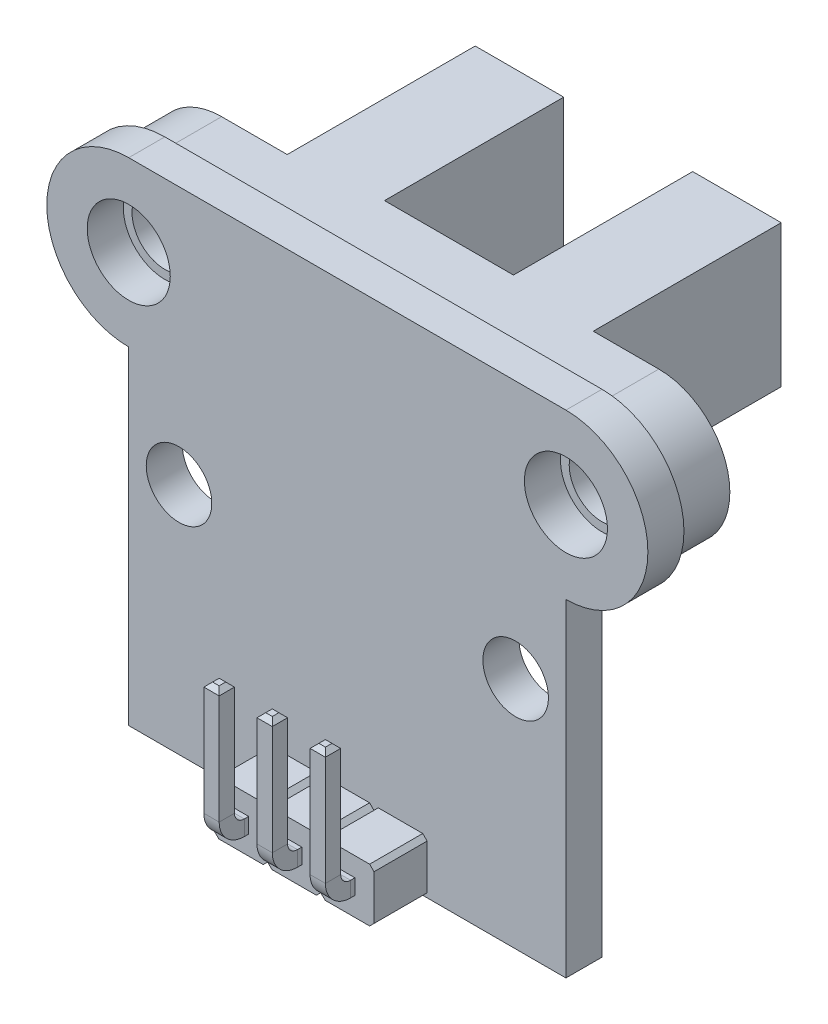
SolidWorks part; units mm, degrees
ref_plane "Ön Düzlem" through (0, 0, 0) normal (0, 0, 1) x (1, 0, 0)
ref_plane "Üst Düzlem" through (0, 0, 0) normal (0, 1, 0) x (1, 0, 0)
ref_plane "Sağ Düzlem" through (0, 0, 0) normal (1, 0, 0) x (0, 0, -1)
sketch "Sketch1" plane through (0, 0, 0) normal (0, 0, 1) x (1, 0, 0)
  line L0 (-10, 0) -> (10, 0) construction
  line L1 (-10, 3.75) -> (10, 3.75)
  line L2 (-10, -3.75) -> (10, -3.75)
  line L3 (10, -3.75) -> (10, -18.75)
  line L4 (10, -18.75) -> (-10, -18.75)
  line L5 (-10, -18.75) -> (-10, -3.75)
  arc A0 (-10, 3.75) -> (-10, -3.75) centre (-10, 0) ccw
  arc A1 (10, -3.75) -> (10, 3.75) centre (10, 0) ccw
  point P2 (0, 0)
  dimension "D1" = 27.5
  dimension "D2" = 7.5
  dimension "D3" = 15
sketch "Sketch2" plane through (0, 0, 0) normal (0, 0, 1) x (1, 0, 0)
  line L0 (-10, -18.75) -> (-10, -3.75) construction
  line L1 (10, -18.75) -> (-10, -18.75) construction
  line L2 (10, -3.75) -> (10, -18.75) construction
  line L3 (-10, 3.75) -> (10, 3.75) construction
  line L4 (-10, -18.75) -> (-10, -3.75)
  line L5 (10, -18.75) -> (-10, -18.75)
  line L6 (10, -3.75) -> (10, -18.75)
  line L7 (-10, 3.75) -> (10, 3.75)
  line L8 (0, 0) -> (0, -18.75) construction
  arc A0 (10, -3.75) -> (10, 3.75) centre (10, 0) ccw construction
  arc A1 (-10, 3.75) -> (-10, -3.75) centre (-10, 0) ccw construction
  arc A2 (10, -3.75) -> (10, 3.75) centre (10, 0) ccw
  arc A3 (-10, 3.75) -> (-10, -3.75) centre (-10, 0) ccw
  circle A4 centre (10, 0) radius 1.9
  circle A5 centre (-10, 0) radius 1.9
  circle A6 centre (7.7, -8.05) radius 1.5
  circle A7 centre (-7.7, -8.05) radius 1.5
  dimension "D1" = 3.8
  dimension "D2" = 0.8
  dimension "D3" = 9.2
  dimension "D4" = 3
extrude "Boss-Extrude1" add sketch "Sketch2" along normal blind 1.65
sketch "Sketch3" plane through (0, 0, 1.65) normal (0, 0, 1) x (1, 0, 0)
  line L0 (-10, -18.75) -> (10, -18.75) construction
  line L1 (3.45, -18.75) -> (1.4167, -18.75)
  line L2 (3.65, -18.55) -> (3.65, -16.5)
  line L3 (3.45, -16.3) -> (1.4167, -16.3)
  line L4 (-3.65, -18.55) -> (-3.65, -16.5)
  line L5 (1.2167, -16.3) -> (1.2167, -18.75) construction
  line L6 (-1.2167, -16.3) -> (-1.2167, -18.75) construction
  line L7 (-1.4167, -16.3) -> (-1.2167, -16.5)
  line L8 (-1.4167, -18.75) -> (-1.2167, -18.55)
  line L9 (-1.2167, -17.525) -> (-0.4992, -17.525) construction
  line L10 (-1.0167, -18.75) -> (-1.2167, -18.55)
  line L11 (-1.0167, -16.3) -> (-1.2167, -16.5)
  line L12 (0, 18.75) -> (0, -18.75) construction
  line L13 (1.0167, -18.75) -> (1.2167, -18.55)
  line L14 (1.4167, -18.75) -> (1.2167, -18.55)
  line L15 (1.0167, -16.3) -> (1.2167, -16.5)
  line L16 (1.4167, -16.3) -> (1.2167, -16.5)
  line L17 (3.65, -16.5) -> (3.45, -16.3)
  line L18 (3.65, -18.55) -> (3.45, -18.75)
  line L19 (-3.45, -18.75) -> (-3.65, -18.55)
  line L20 (-3.45, -16.3) -> (-3.65, -16.5)
  line L21 (-1.4167, -16.3) -> (-3.45, -16.3)
  line L22 (-1.4167, -18.75) -> (-3.45, -18.75)
  line L23 (1.0167, -18.75) -> (-1.0167, -18.75)
  line L24 (1.0167, -16.3) -> (-1.0167, -16.3)
  line L25 (-2.4333, -18.75) -> (-2.4333, -16.3) construction
  line L26 (0.3467, -17.175) -> (0.3467, -17.875)
  line L27 (-2.0833, -17.175) -> (-2.7833, -17.175)
  line L28 (-2.0833, -17.175) -> (-2.0833, -17.875)
  line L29 (-2.0833, -17.875) -> (-2.7833, -17.875)
  line L30 (-2.7833, -17.175) -> (-2.7833, -17.875)
  line L31 (-2.0833, -17.175) -> (-2.7833, -17.875) construction
  line L32 (-2.0833, -17.875) -> (-2.7833, -17.175) construction
  line L33 (0.3467, -17.175) -> (-0.3533, -17.175)
  line L34 (-0.3533, -17.175) -> (-0.3533, -17.875)
  line L35 (0.3467, -17.875) -> (-0.3533, -17.875)
  line L36 (2.7767, -17.175) -> (2.7767, -17.875)
  line L37 (2.7767, -17.175) -> (2.0767, -17.175)
  line L38 (2.0767, -17.175) -> (2.0767, -17.875)
  line L39 (2.7767, -17.875) -> (2.0767, -17.875)
  point P0 (3.65, -18.75)
  point P1 (-3.65, -16.3)
  point P2 (3.65, -16.3)
  point P3 (-3.65, -18.75)
  point P39 (-2.4333, -17.525)
extrude "Boss-Extrude2" add sketch "Sketch3" along normal blind 2.43 separate body
sketch "Sketch4" plane through (0, 0, 1.65) normal (0, 0, 1) x (1, 0, 0)
  line L0 (2.7767, -17.175) -> (2.0767, -17.175) construction
  line L1 (2.7767, -17.875) -> (2.7767, -17.175) construction
  line L2 (2.0767, -17.875) -> (2.7767, -17.875) construction
  line L3 (2.0767, -17.175) -> (2.0767, -17.875) construction
  line L4 (0.3467, -17.175) -> (-0.3533, -17.175) construction
  line L5 (0.3467, -17.875) -> (0.3467, -17.175) construction
  line L6 (-0.3533, -17.875) -> (0.3467, -17.875) construction
  line L7 (-0.3533, -17.175) -> (-0.3533, -17.875) construction
  line L8 (-2.7833, -17.875) -> (-2.0833, -17.875) construction
  line L9 (-2.7833, -17.175) -> (-2.7833, -17.875) construction
  line L10 (-2.0833, -17.175) -> (-2.7833, -17.175) construction
  line L11 (-2.0833, -17.875) -> (-2.0833, -17.175) construction
  line L12 (2.7767, -17.175) -> (2.0767, -17.175)
  line L13 (2.7767, -17.875) -> (2.7767, -17.175)
  line L14 (2.0767, -17.875) -> (2.7767, -17.875)
  line L15 (2.0767, -17.175) -> (2.0767, -17.875)
  line L16 (0.3467, -17.175) -> (-0.3533, -17.175)
  line L17 (0.3467, -17.875) -> (0.3467, -17.175)
  line L18 (-0.3533, -17.875) -> (0.3467, -17.875)
  line L19 (-0.3533, -17.175) -> (-0.3533, -17.875)
  line L20 (-2.7833, -17.875) -> (-2.0833, -17.875)
  line L21 (-2.7833, -17.175) -> (-2.7833, -17.875)
  line L22 (-2.0833, -17.175) -> (-2.7833, -17.175)
  line L23 (-2.0833, -17.875) -> (-2.0833, -17.175)
extrude "Cut-Extrude1" cut sketch "Sketch4" against normal blind 2.43
ref_plane "Plane1" through (0, 0, -1) normal (0, 0, 1) x (1, 0, 0)
sketch "Sketch5" plane through (0, 0, -1) normal (0, 0, 1) x (1, 0, 0)
  line L0 (-2.0833, -17.175) -> (-2.7833, -17.175) construction
  line L1 (-2.0833, -17.875) -> (-2.0833, -17.175) construction
  line L2 (-2.7833, -17.875) -> (-2.0833, -17.875) construction
  line L3 (-2.7833, -17.175) -> (-2.7833, -17.875) construction
  line L4 (-2.0833, -17.175) -> (-2.7833, -17.175)
  line L5 (-2.0833, -17.875) -> (-2.0833, -17.175)
  line L6 (-2.7833, -17.875) -> (-2.0833, -17.875)
  line L7 (-2.7833, -17.175) -> (-2.7833, -17.875)
ref_plane "Plane2" through (-2.4333, 0, 0) normal (-1, 0, 0) x (0, 0, 1)
sketch "Sketch6" plane through (-2.4333, 0, 0) normal (-1, 0, 0) x (0, 0, 1)
  line L0 (-1, -17.525) -> (4.28, -17.525)
  line L1 (-1, -17.875) -> (-1, -17.175) construction
  line L2 (5.08, -16.725) -> (5.08, -11.525)
  line L3 (4.08, -16.5) -> (4.08, -18.55) construction
  arc A0 (4.28, -17.525) -> (5.08, -16.725) centre (4.28, -16.725) ccw
  point P9 (5.08, -17.525)
  dimension "D3" = 0.8
  dimension "D1" = 1
  dimension "D2" = 6
sweep "Sweep1" add profiles "Sketch5" path "Sketch6"
chamfer "Chamfer1" distance 0.2 angle 45 8 edges at (-2.4333, -17.175, -1) (-2.7833, -17.525, -1) (-2.4333, -17.875, -1) (-2.0833, -11.525, 5.08) (-2.4333, -11.525, 4.73) (-2.7833, -11.525, 5.08) (-2.4333, -11.525, 5.43) (-2.0833, -17.525, -1)
pattern_linear "LPattern1" count 3 spacing 2.43 along (1, 0, 0) of bodies 104
sketch "Sketch7" plane through (0, 0, 0) normal (0, 0, -1) x (-1, 0, 0)
  line L0 (10, 0) -> (-10, 0) construction
  line L1 (10, -3.25) -> (-10, -3.25)
  line L2 (10, 3.25) -> (-10, 3.25)
  arc A0 (10, -3.25) -> (10, 3.25) centre (10, 0) ccw
  arc A1 (-10, 3.25) -> (-10, -3.25) centre (-10, 0) ccw
  arc A3 (-10, 3.75) -> (-10, -3.75) centre (-10, 0) ccw construction
  circle A4 centre (-10, 0) radius 1.5
  circle A5 centre (10, 0) radius 1.5
  point P2 (0, 0)
  dimension "D1" = 0.5
  dimension "D2" = 3
extrude "Boss-Extrude3" add sketch "Sketch7" along normal blind 2.6 separate body
sketch "Sketch8" plane through (0, 0, -2.6) normal (0, 0, -1) x (-1, 0, 0)
  line L0 (-10, -3.25) -> (10, -3.25) construction
  line L1 (7, 3.25) -> (-7, 3.25)
  line L2 (7, 3.25) -> (7, -3.25)
  line L3 (7, -3.25) -> (-7, -3.25)
  line L4 (-7, 3.25) -> (-7, -3.25)
  line L5 (7, 3.25) -> (-7, -3.25) construction
  line L6 (7, -3.25) -> (-7, 3.25) construction
  point P0 (0, 0)
  dimension "D1" = 14
extrude "Boss-Extrude4" add sketch "Sketch8" along normal blind 8.6
sketch "Sketch9" plane through (0, 0, -11.2) normal (0, 0, -1) x (-1, 0, 0)
  line L0 (-7, -3.25) -> (7, -3.25) construction
  line L1 (2.95, 3.25) -> (-2.95, 3.25)
  line L2 (2.95, 3.25) -> (2.95, -3.25)
  line L3 (2.95, -3.25) -> (-2.95, -3.25)
  line L4 (-2.95, 3.25) -> (-2.95, -3.25)
  line L5 (2.95, 3.25) -> (-2.95, -3.25) construction
  line L6 (2.95, -3.25) -> (-2.95, 3.25) construction
  point P0 (0, 0)
  dimension "D1" = 5.9
extrude "Cut-Extrude2" cut sketch "Sketch9" against normal blind 8.2
sketch "Sketch10" plane through (0, 0, -11.2) normal (0, 0, -1) x (-1, 0, 0)
  line L0 (-4.975, 3.25) -> (-4.975, -3.25) construction
  line L1 (-2.95, 3.25) -> (-7, 3.25) construction
  line L2 (-7, -3.25) -> (-2.95, -3.25) construction
  line L3 (-5.1032, -1.8452) -> (-5.1032, -0.9434)
  line L4 (-6.273, 1.1361) -> (-5.2054, 1.1361)
  line L5 (-5.2054, 1.1361) -> (-5.2054, 2.2037)
  line L6 (-5.2054, 2.2037) -> (-4.7446, 2.2037)
  line L7 (-5.1032, -0.7766) -> (-6.273, 1.1361)
  line L8 (-5.1032, -0.7766) -> (-6.3856, -0.7766)
  line L9 (-6.3856, -0.7766) -> (-6.3856, -0.9434)
  line L10 (-6.3856, -0.9434) -> (-5.1032, -0.9434)
  line L11 (-5.1032, -1.8452) -> (-4.8468, -1.8452)
  line L12 (-3.5644, -0.9434) -> (-4.8468, -0.9434)
  line L13 (-3.5644, -0.7766) -> (-3.5644, -0.9434)
  line L14 (-4.8468, -0.7766) -> (-3.5644, -0.7766)
  line L15 (-4.8468, -0.7766) -> (-3.677, 1.1361)
  line L16 (-4.7446, 1.1361) -> (-4.7446, 2.2037)
  line L17 (-3.677, 1.1361) -> (-4.7446, 1.1361)
  line L18 (-4.8468, -1.8452) -> (-4.8468, -0.9434)
  point P16 (-4.975, -1.8452)
  point P18 (-4.975, 2.2037)
extrude "Boss-Extrude5" add sketch "Sketch10" along normal blind 0.1
sketch "Sketch11" plane through (0, 0, -11.2) normal (0, 0, -1) x (-1, 0, 0)
  line L0 (4.15, 3.25) -> (4.15, -3.25) construction
  line L1 (2.95, -3.25) -> (2.95, 3.25) construction
  line L3 (7, 3.25) -> (2.95, 3.25) construction
  text T0 "WYC\r\nH206" font "Consolas" height in points 3
  dimension "D1" = 1.2
extrude "Boss-Extrude6" add sketch "Sketch11" along normal blind 0.1
equation "\"D4@Sketch3\"=\"D3@Sketch3\""
equation "\"D6@Sketch3\"=\"D5@Sketch3\""
